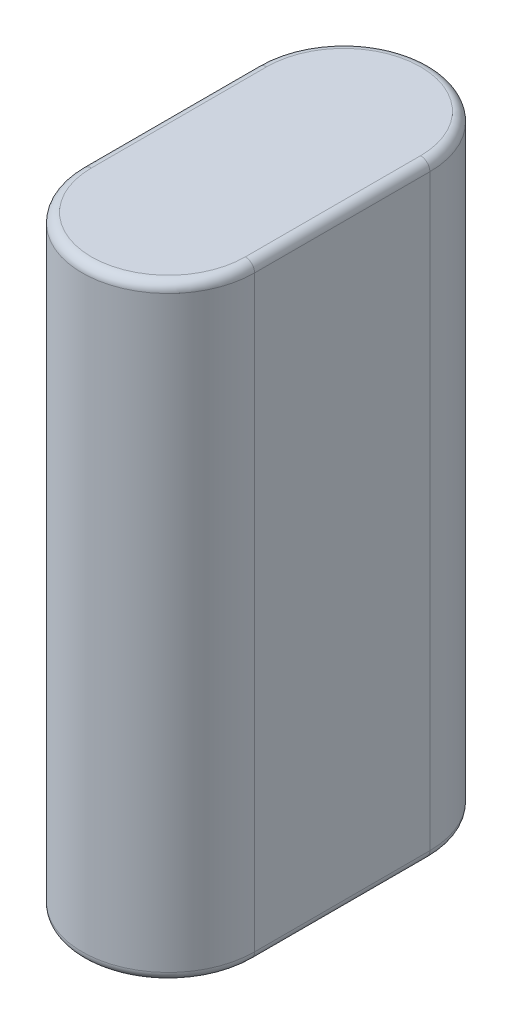
SolidWorks part; units mm, degrees
ref_plane "前视基准面" through (0, 0, 0) normal (0, 0, 1) x (1, 0, 0)
ref_plane "上视基准面" through (0, 0, 0) normal (0, 1, 0) x (1, 0, 0)
ref_plane "右视基准面" through (0, 0, 0) normal (1, 0, 0) x (0, 0, -1)
other "Configuration Table"
sketch "草图1" plane through (0, 0, 0) normal (0, 1, 0) x (1, 0, 0)
  line L0 (0, 9.45) -> (0, -9.45) construction
  line L1 (9.3, 9.45) -> (9.3, -9.45)
  line L2 (-9.3, 9.45) -> (-9.3, -9.45)
  line L3 (-20.8664, 0) -> (48.4538, 0) construction
  arc A0 (9.3, 9.45) -> (-9.3, 9.45) centre (0, 9.45) ccw
  arc A1 (-9.3, -9.45) -> (9.3, -9.45) centre (0, -9.45) ccw
  point P3 (0, 0)
  dimension "D1" = 9.3
  dimension "D2" = 18.9
extrude "凸台-拉伸1" add sketch "草图1" along normal blind 65.4
fillet "圆角1" radius 1 8 edges at (0, 0, 18.75) (-9.3, 0, 0) (0, 0, -18.75) (0, 65.4, 18.75) (-9.3, 65.4, 0) (0, 65.4, -18.75) (9.3, 0, 0) (9.3, 65.4, 0)
